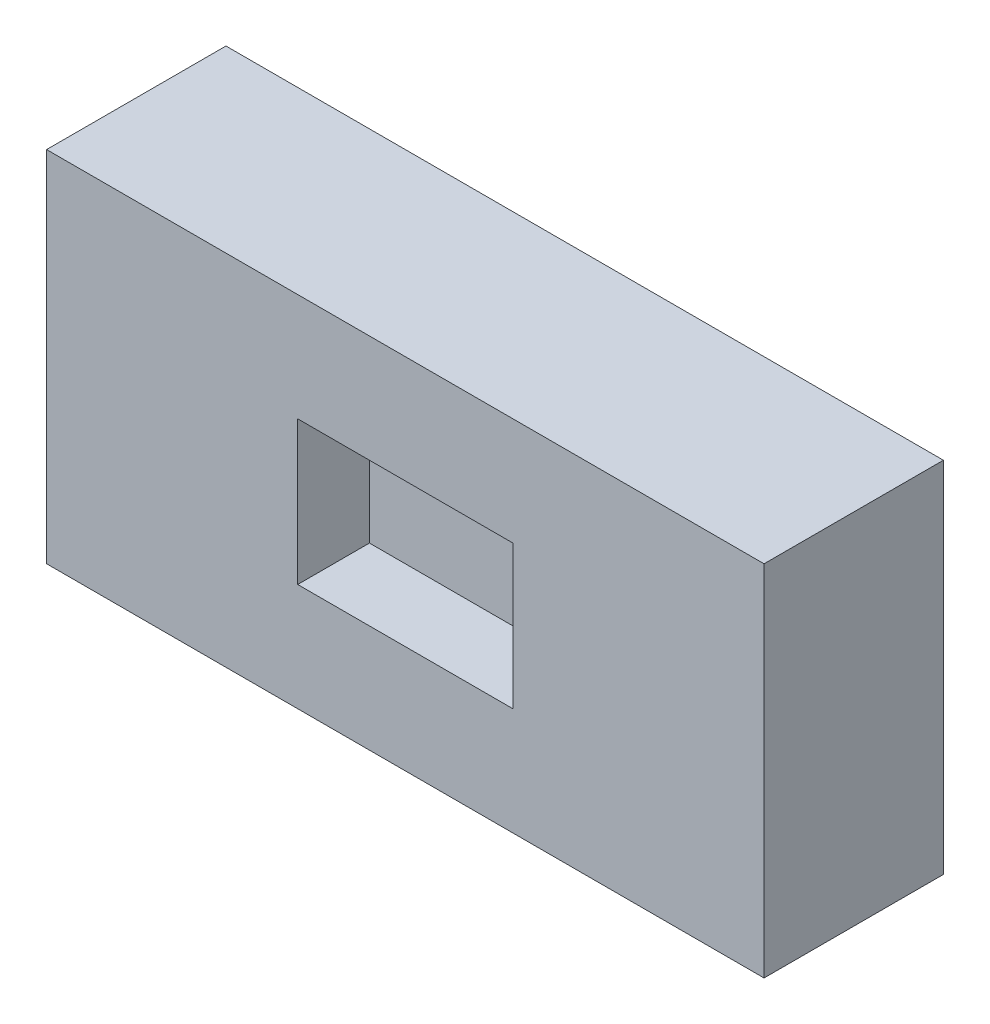
SolidWorks part; units mm, degrees
ref_plane "Front Plane" through (0, 0, 0) normal (0, 0, 1) x (1, 0, 0)
ref_plane "Top Plane" through (0, 0, 0) normal (0, 1, 0) x (1, 0, 0)
ref_plane "Right Plane" through (0, 0, 0) normal (1, 0, 0) x (0, 0, -1)
sketch "RectangleSketch" plane through (0, 0, 0) normal (0, 0, 1) x (1, 0, 0)
  line L1 (0, 0) -> (40, 0)
  line L2 (0, 0) -> (0, 20)
  line L3 (0, 20) -> (40, 20)
  line L4 (40, 0) -> (40, 20)
  dimension "width_mm" = 40
  dimension "height_mm" = 20
extrude "BlindBoss" add sketch "RectangleSketch" along normal blind 10 separate body
sketch "CutSketch" plane through (0, 0, 10) normal (0, 0, 1) x (1, 0, 0)
  line L1 (14, 6) -> (26, 6)
  line L2 (14, 6) -> (14, 14)
  line L3 (14, 14) -> (26, 14)
  line L4 (26, 6) -> (26, 14)
  dimension "cut_width_mm" = 12
  dimension "cut_height_mm" = 8
  dimension "cut_left_mm" = 14
  dimension "cut_bottom_mm" = 6
extrude "BlindCut" cut sketch "CutSketch" against normal blind 4
equation "\"cut_left_mm@CutSketch\" = (\"width_mm@RectangleSketch\" - \"cut_width_mm@CutSketch\") / 2"
equation "\"cut_bottom_mm@CutSketch\" = (\"height_mm@RectangleSketch\" - \"cut_height_mm@CutSketch\") / 2"
